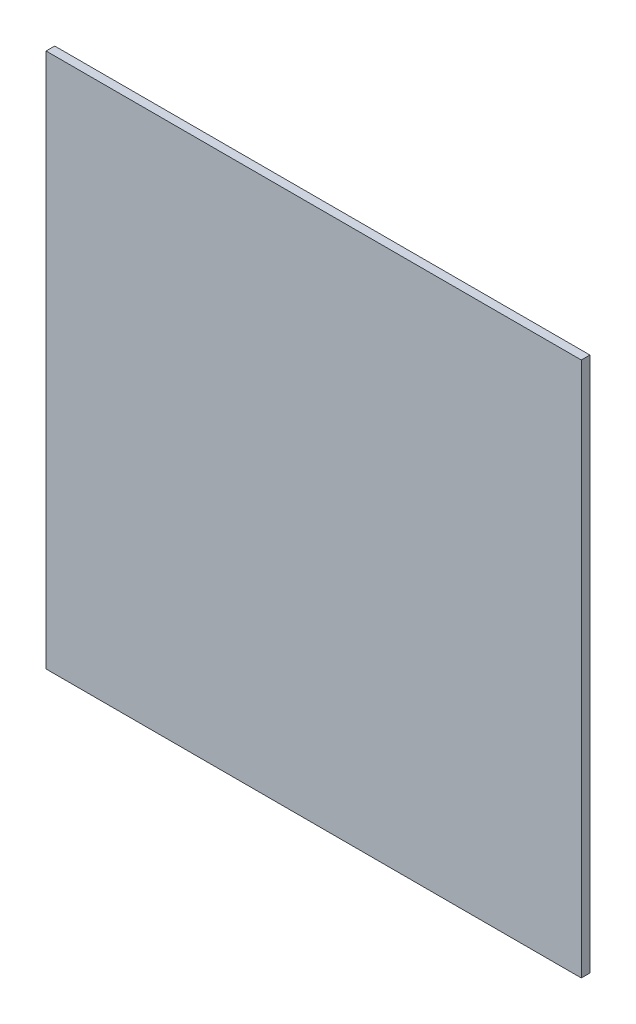
SolidWorks part; units mm, degrees
ref_plane "Plan de face" through (0, 0, 0) normal (0, 0, 1) x (1, 0, 0)
ref_plane "Plan de dessus" through (0, 0, 0) normal (0, 1, 0) x (1, 0, 0)
ref_plane "Plan de droite" through (0, 0, 0) normal (1, 0, 0) x (0, 0, -1)
sketch "Esquisse1" plane through (0, 0, 0) normal (0, 0, 1) x (1, 0, 0)
  line L1 (0, 0) -> (620, 0)
  line L2 (0, 0) -> (0, 620)
  line L3 (0, 620) -> (620, 620)
  line L4 (620, 0) -> (620, 620)
  dimension "D1" = 620
  dimension "D2" = 620
extrude "Boss.-Extru.1" add sketch "Esquisse1" along normal blind 10
